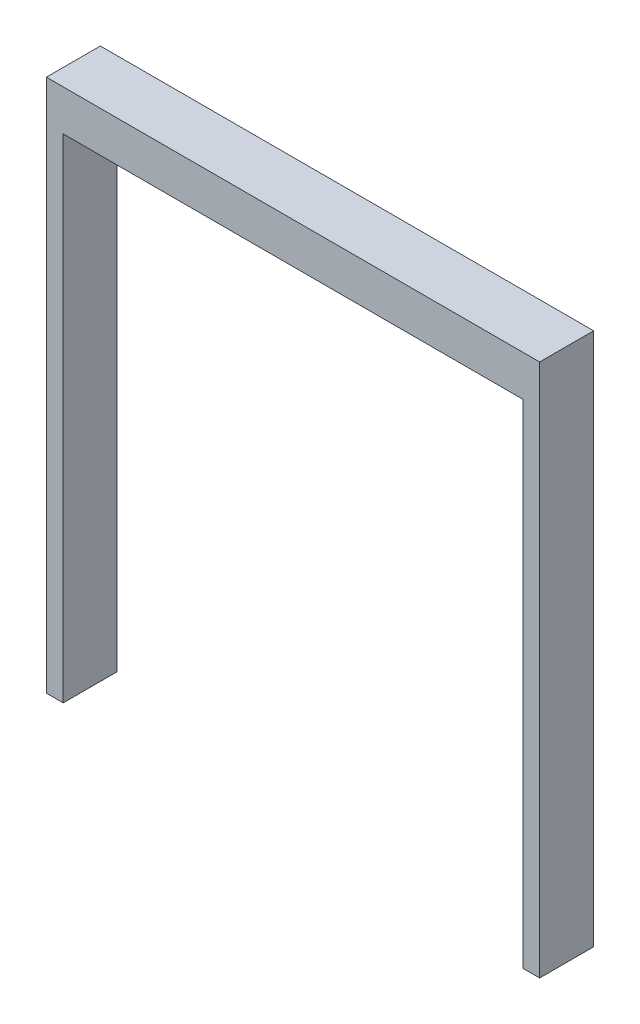
SolidWorks part; units mm, degrees
ref_plane "Front Plane" through (0, 0, 0) normal (0, 0, 1) x (1, 0, 0)
ref_plane "Top Plane" through (0, 0, 0) normal (0, 1, 0) x (1, 0, 0)
ref_plane "Right Plane" through (0, 0, 0) normal (1, 0, 0) x (0, 0, -1)
sketch "Sketch1" plane through (0, 0, 0) normal (0, 0, 1) x (1, 0, 0)
  line L0 (-30.8579, 26.6851) -> (17.5921, 26.6851)
  line L1 (17.5921, 26.6851) -> (17.5921, -25.7149)
  line L2 (17.5921, -25.7149) -> (15.9421, -25.7149)
  line L3 (15.9421, -25.7149) -> (15.9421, 22.6851)
  line L4 (15.9421, 22.6851) -> (-29.2079, 22.6851)
  line L5 (-29.2079, 22.6851) -> (-29.2079, -25.7149)
  line L6 (-29.2079, -25.7149) -> (-30.8579, -25.7149)
  line L7 (-30.8579, -25.7149) -> (-30.8579, 26.6851)
  dimension "D1" = 45.15
  dimension "D2" = 48.45
  dimension "D3" = 1.65
  dimension "D4" = 48.4
  dimension "D5" = 4
  dimension "D6" = 48.4
extrude "Boss-Extrude1" add sketch "Sketch1" along normal blind 5.3
